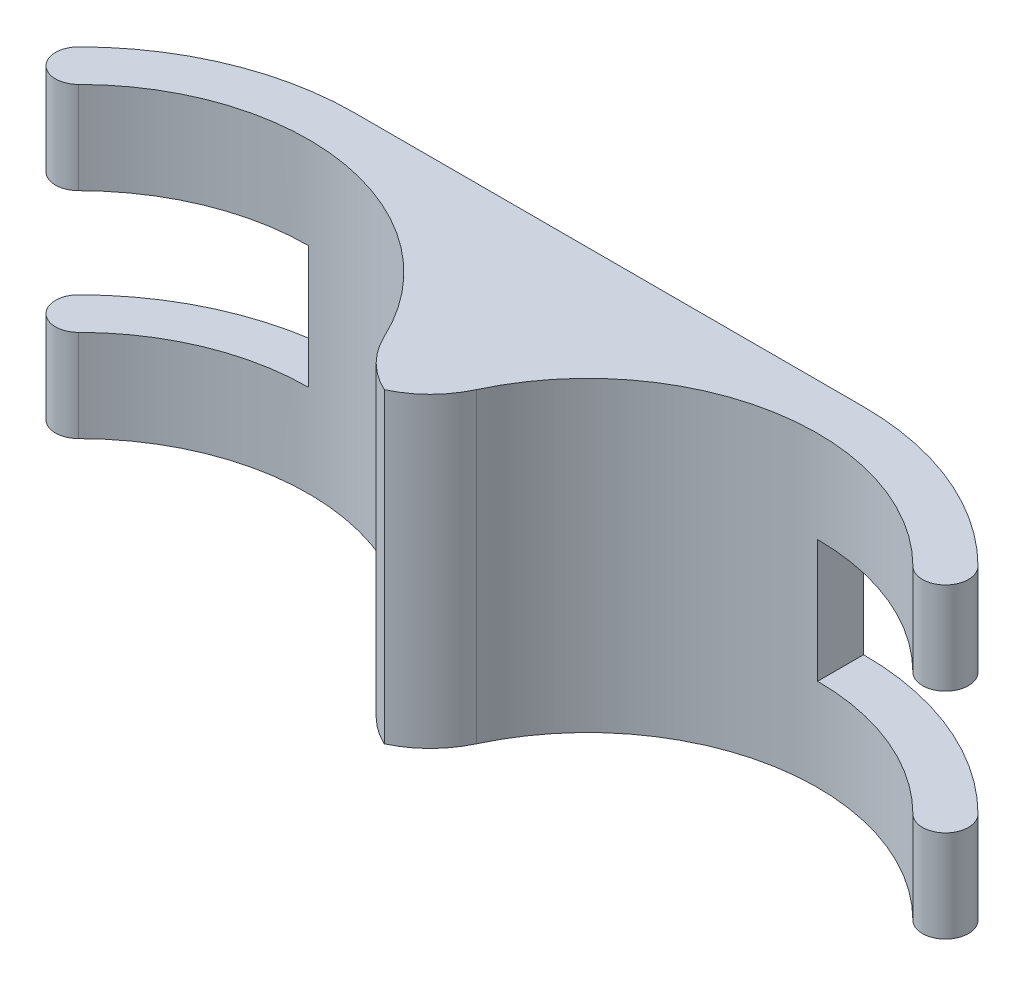
SolidWorks part; units mm, degrees
material "A286 Iron Base Superalloy"
ref_plane "Front Plane" through (0, 0, 0) normal (0, 0, 1) x (1, 0, 0)
ref_plane "Top Plane" through (0, 0, 0) normal (0, 1, 0) x (1, 0, 0)
ref_plane "Right Plane" through (0, 0, 0) normal (1, 0, 0) x (0, 0, -1)
sketch "Sketch1" plane through (0, 0, 0) normal (0, 1, 0) x (1, 0, 0)
  line L0 (0, 0) -> (5.3033, 5.3033) construction
  line L1 (0, 0) -> (0, 7.5) construction
  line L2 (0, 0) -> (-6.7973, 3.1696) construction
  line L3 (0, 0) -> (6.364, 6.364) construction
  line L4 (0, 0) -> (0, 1.5) construction
  line L5 (5.3033, 5.3033) -> (6.364, 6.364) construction
  line L6 (0, 9) -> (-16.5946, 9)
  line L7 (-6.7973, 3.1696) -> (-8.2973, 3.1696) construction
  line L8 (-8.2973, 3.1696) -> (-8.2973, 1.6696) construction
  line L9 (-8.2973, 1.6696) -> (-8.2973, 9) construction
  arc A0 (-6.7973, 3.1696) -> (5.3033, 5.3033) centre (0, 0) cw
  arc A1 (0, 9) -> (6.364, 6.364) centre (0, 0) cw
  arc A2 (6.364, 6.364) -> (5.3033, 5.3033) centre (5.8336, 5.8336) cw
  arc A3 (-6.7973, 3.1696) -> (-8.2973, 1.6696) centre (-9.6079, 4.4802) cw
  arc A4 (-22.9586, 6.364) -> (-21.8979, 5.3033) centre (-22.4282, 5.8336) ccw
  arc A5 (-16.5946, 9) -> (-22.9586, 6.364) centre (-16.5946, 0) ccw
  arc A6 (-9.7973, 3.1696) -> (-21.8979, 5.3033) centre (-16.5946, 0) ccw
  arc A7 (-9.7973, 3.1696) -> (-8.2973, 1.6696) centre (-6.9867, 4.4802) ccw
  dimension "D1" = 7.5
  dimension "D2" = 7.5
  dimension "D7" = 45
  dimension "D8" = 1.5
  dimension "D5" = 9
  dimension "D3" = 45
  dimension "D4" = 65
  dimension "D6" = 1.5
  dimension "D9" = 1.5
extrude "Boss-Extrude2" add sketch "Sketch1" along normal blind 10 contours A6 A7 A3 A0 A2 A1 L6 A5 A4
sketch "Sketch2" plane through (0, 0, -9) normal (0, 0, -1) x (-1, 0, 0)
  line L0 (-6.5836, 10) -> (-6.5836, 0) construction
  line L1 (-6.5836, 7) -> (0, 7)
  line L2 (-6.5836, 7) -> (-6.5836, 3)
  line L3 (-6.5836, 3) -> (0, 3)
  line L4 (0, 7) -> (0, 3)
  line L5 (0, 10) -> (0, 0) construction
  line L6 (8.2973, 10) -> (8.2973, 0) construction
  line L7 (0, 10) -> (16.5946, 10) construction
  line L8 (0, 10) -> (-6.364, 10) construction
  line L9 (16.5946, 7) -> (16.5946, 3)
  line L10 (23.1782, 3) -> (16.5946, 3)
  line L11 (23.1782, 7) -> (23.1782, 3)
  line L12 (23.1782, 7) -> (16.5946, 7)
  dimension "D1" = 4
  dimension "D2" = 3
extrude "Cut-Extrude1" cut sketch "Sketch2" against normal blind 20
sketch "Sketch3" plane through (0, 0, -9) normal (0, 0, -1) x (-1, 0, 0)
  line L0 (7.9092, -4.5) -> (7.9092, 20.5) construction
  line L1 (7.9092, 20.5) -> (7.9092, -29.5) construction
sketch "Sketch4" plane through (0, 0, -9) normal (0, 0, -1) x (-1, 0, 0)
  line L0 (8.2973, 10) -> (8.2973, 0) construction
  line L1 (0, 0) -> (16.5946, 0) construction
